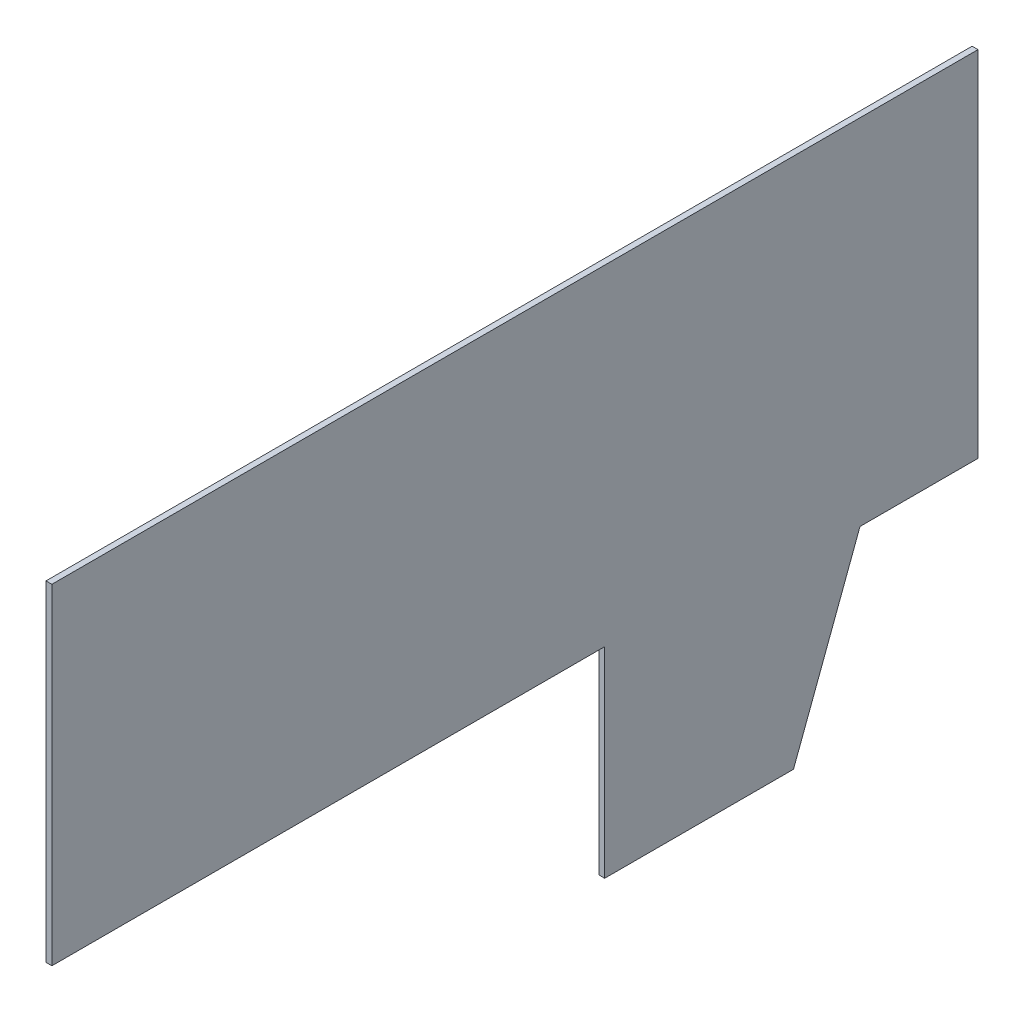
SolidWorks part; units mm, degrees
material "6061-T6 (SS)"
ref_plane "X-Y Datum" through (0, 0, 0) normal (0, 0, 1) x (1, 0, 0)
ref_plane "X-Z Datum" through (0, 0, 0) normal (0, 1, 0) x (1, 0, 0)
ref_plane "Y-Z Datum" through (0, 0, 0) normal (1, 0, 0) x (0, 0, -1)
sketch "Sketch1" plane through (0, 0, 0) normal (1, 0, 0) x (0, 0, -1)
  line L1 (-249.174, 88.9) -> (249.174, 88.9)
  line L2 (-249.174, 88.9) -> (-249.174, -88.9)
  line L3 (-249.174, -88.9) -> (249.174, -88.9)
  line L4 (249.174, 88.9) -> (249.174, -88.9)
  line L5 (-249.174, 88.9) -> (249.174, -88.9) construction
  line L6 (-249.174, -88.9) -> (249.174, 88.9) construction
  point P0 (0, 0)
  dimension "D1" = 177.8
  dimension "D2" = 498.348
extrude "Boss-Extrude1" add sketch "Sketch1" along normal mid plane 3.175
sketch "Sketch2" plane through (1.5875, 0, 0) normal (1, 0, 0) x (0, 0, -1)
  line L0 (249.174, -88.9) -> (249.174, -101.6)
  line L1 (249.174, -101.6) -> (185.674, -101.6)
  line L2 (185.674, -101.6) -> (149.8854, -196.85)
  line L3 (149.8854, -196.85) -> (48.2854, -196.85)
  line L4 (48.2854, -196.85) -> (48.2854, -88.9)
  line L5 (-249.174, -88.9) -> (249.174, -88.9) construction
  line L6 (48.2854, -88.9) -> (249.174, -88.9)
  line L8 (48.2854, -76.2) -> (48.2854, 88.9)
  line L10 (249.174, -88.9) -> (249.174, 88.9) construction
  line M10 (-249.174, -88.9) -> (249.174, -88.9)
  dimension "D1" = 12.7
  dimension "D2" = 63.5
  dimension "D3" = 107.95
  dimension "D4" = 101.6
extrude "Boss-Extrude2" add sketch "Sketch2" against normal blind 3.175 contours L4 L3 L2 L1 L0 M10
